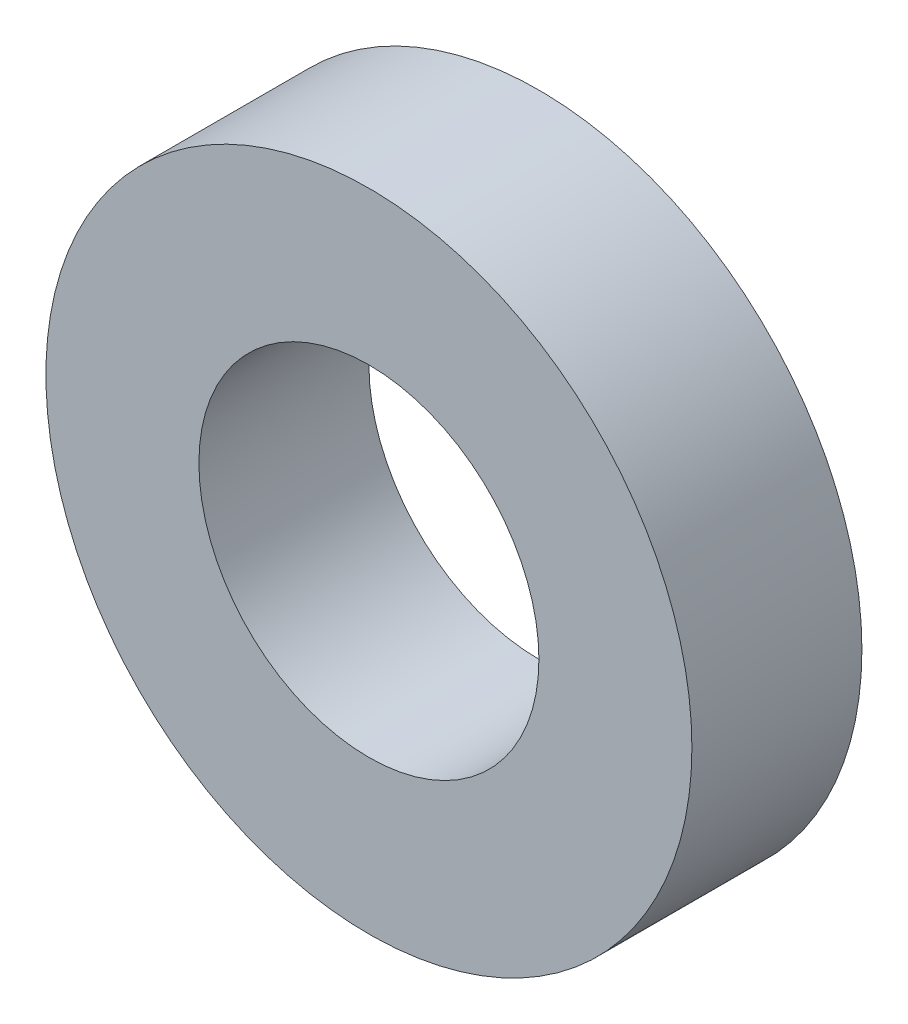
SolidWorks part; units mm, degrees
ref_plane "前视基准面" through (0, 0, 0) normal (0, 0, 1) x (1, 0, 0)
ref_plane "上视基准面" through (0, 0, 0) normal (0, 1, 0) x (1, 0, 0)
ref_plane "右视基准面" through (0, 0, 0) normal (1, 0, 0) x (0, 0, -1)
sketch "草图1" plane through (0, 0, 0) normal (0, 0, 1) x (1, 0, 0)
  circle A0 centre (0, 0) radius 5
  circle A1 centre (0, 0) radius 9.5
  dimension "D1" = 19
  dimension "D2" = 10
extrude "凸台-拉伸1" add sketch "草图1" along normal blind 5
